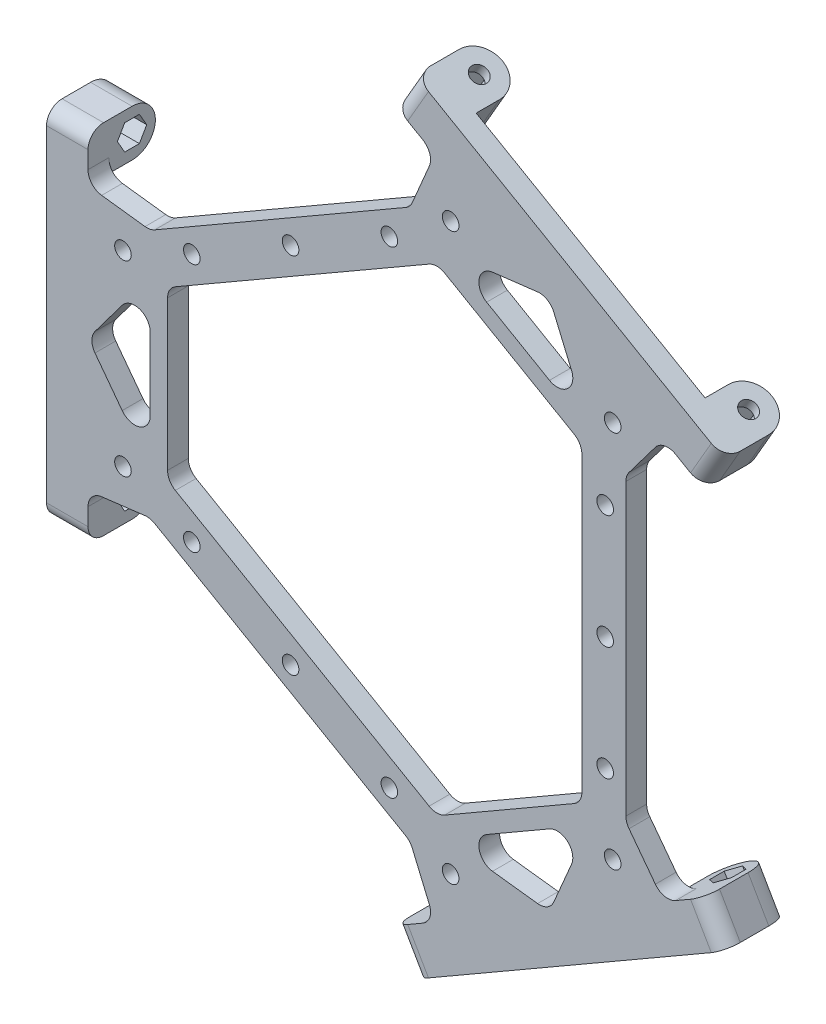
SolidWorks part; units mm, degrees
material "ABS"
ref_plane "前视基准面" through (0, 0, 0) normal (0, 0, 1) x (1, 0, 0)
ref_plane "上视基准面" through (0, 0, 0) normal (0, 1, 0) x (1, 0, 0)
ref_plane "右视基准面" through (0, 0, 0) normal (1, 0, 0) x (0, 0, -1)
sketch "草图1" plane through (0, 0, 0) normal (0, 0, 1) x (1, 0, 0)
  line L0 (0, 0) -> (-67.3124, 0) construction
  line L1 (134.6248, 0) -> (-67.3124, 116.5885)
  line L2 (-67.3124, 116.5885) -> (-67.3124, -116.5885)
  line L3 (-67.3124, -116.5885) -> (134.6248, 0)
  line L4 (-67.3124, 116.5885) -> (-67.3124, 85.5885) construction
  line L5 (-67.3124, 85.5885) -> (-67.3124, 30) construction
  line L6 (0, 0) -> (117.3042, 0) construction
  line L7 (117.3042, 10) -> (117.3042, -10)
  line L8 (-49.9919, -106.5885) -> (-67.3124, -96.5885)
  line L9 (-58.6521, -101.5885) -> (-67.3124, -116.5885) construction
  line L10 (0, 0) -> (-58.6521, -101.5885) construction
  line L11 (-67.3124, 96.5885) -> (-49.9919, 106.5885)
  line L12 (85.9645, 5) -> (-38.6521, 76.9474)
  line L13 (-47.3124, 71.9474) -> (-47.3124, -71.9474)
  line L14 (-38.6521, -76.9474) -> (85.9645, -5)
  line L15 (85.9645, 5) -> (85.9645, -5)
  line L16 (-38.6521, -76.9474) -> (-47.3124, -71.9474)
  line L17 (-47.3124, 71.9474) -> (-38.6521, 76.9474)
  line L18 (94.6248, 0) -> (-47.3124, 81.9474) construction
  line L19 (-47.3124, 81.9474) -> (-47.3124, -81.9474) construction
  line L20 (-47.3124, -81.9474) -> (94.6248, 0) construction
  line L24 (117.3042, 0) -> (134.6248, 0) construction
  line L25 (-58.6521, 101.5885) -> (-67.3124, 116.5885) construction
  line L26 (2.8479, -52.9874) -> (-47.3124, -24.0274)
  line L27 (60.9645, -25.5) -> (60.9645, 25.5) construction
  line L28 (60.9645, 0) -> (40.4645, 0) construction
  line L29 (81.4645, 4.5) -> (81.4645, 7.5981)
  line L30 (81.4645, -4.5) -> (81.4645, -7.5981)
  line L31 (-52.5659, -40.0468) -> (-8.3986, -65.5468) construction
  line L32 (44.4645, 28.96) -> (44.4645, -28.96)
  line L33 (-36.8351, -72.8003) -> (-34.1521, -74.3494)
  line L34 (-44.6294, -68.3003) -> (-47.3124, -66.7513)
  line L35 (0, 0) -> (-58.6521, 101.5885) construction
  line L36 (-47.3124, 24.0274) -> (2.8479, 52.9874)
  line L37 (-8.3986, 65.5468) -> (-52.5659, 40.0468) construction
  line L38 (-44.6294, 68.3003) -> (-47.3124, 66.7513)
  line L39 (-36.8351, 72.8003) -> (-34.1521, 74.3494)
  line L40 (-47.3124, 24.0274) -> (-59.3124, 25.5)
  line L41 (40.4645, 22) -> (40.4645, -22) construction
  line L42 (-47.3124, 16) -> (-59.3124, 0)
  line L43 (-67.3124, 25.5) -> (-47.3124, 25.5) construction
  line L44 (-67.3124, 34.5) -> (-59.3124, 34.5)
  line L45 (-59.3124, 34.5) -> (-59.3124, 25.5)
  line L46 (-59.3124, 25.5) -> (-67.3124, 25.5)
  line L47 (-59.3124, 25.5) -> (-59.3124, -25.5)
  line L48 (-59.3124, -34.5) -> (-59.3124, -25.5)
  line L49 (-59.3124, -25.5) -> (-67.3124, -25.5)
  line L50 (-67.3124, -34.5) -> (-59.3124, -34.5)
  line L51 (-52.5659, 40.0468) -> (-52.5659, 18.0468) construction
  line L52 (-52.5659, -40.0468) -> (-52.5659, -18.0468) construction
  line L53 (60.9645, 25.5) -> (41.9119, 36.5) construction
  line L54 (63.5341, 41.0442) -> (59.5341, 34.116)
  line L55 (-47.3124, -16) -> (-59.3124, 0)
  line L56 (-59.3124, -25.5) -> (-47.3124, -24.0274)
  line L57 (51.7398, 38.616) -> (55.7398, 45.5442)
  line L58 (51.7398, 38.616) -> (7.5725, 64.116)
  line L59 (59.5341, 34.116) -> (51.7398, 38.616)
  line L60 (3.7783, 75.5442) -> (-0.2217, 68.616)
  line L61 (-0.2217, 68.616) -> (7.5725, 64.116)
  line L62 (7.5725, 64.116) -> (11.5725, 71.0442)
  line L63 (7.5725, 64.116) -> (2.8479, 52.9874)
  line L64 (9.7998, 48.9737) -> (29.6562, 51.366)
  line L68 (37.5126, 32.9737) -> (29.6562, 51.366)
  line L69 (-1.1797, -46.0433) -> (-39.2848, -24.0433) construction
  line L70 (44.4645, 28.96) -> (51.7398, 38.616)
  line L71 (-8.3986, -65.5468) -> (10.654, -54.5468) construction
  line L72 (3.7783, -75.5442) -> (-0.2217, -68.616)
  line L73 (7.5725, -64.116) -> (11.5725, -71.0442)
  line L74 (7.5725, -64.116) -> (51.7398, -38.616)
  line L75 (-0.2217, -68.616) -> (7.5725, -64.116)
  line L76 (63.5341, -41.0442) -> (59.5341, -34.116)
  line L77 (59.5341, -34.116) -> (51.7398, -38.616)
  line L78 (51.7398, -38.616) -> (55.7398, -45.5442)
  line L79 (51.7398, -38.616) -> (44.4645, -28.96)
  line L80 (37.5126, -32.9737) -> (29.6562, -51.366)
  line L84 (9.7998, -48.9737) -> (29.6562, -51.366)
  line L85 (-39.2848, 24.0433) -> (-1.1797, 46.0433) construction
  line L86 (2.8479, -52.9874) -> (7.5725, -64.116)
  line L89 (-43.963, 16.1462) -> (7.9985, 46.1462)
  line L90 (35.9645, 30) -> (35.9645, -30)
  line L91 (7.9985, -46.1462) -> (-43.963, -16.1462)
  line L92 (-43.963, 16.1462) -> (-43.963, -16.1462)
  line L93 (7.9985, -46.1462) -> (35.9645, -30)
  line L94 (7.9985, 46.1462) -> (35.9645, 30)
  line L161 (0, 0) -> (-58.6521, -101.5885) construction
  line L162 (0, 0) -> (-58.6521, 101.5885) construction
  circle A0 centre (0, 0) radius 67.3124 construction
  circle A1 centre (-59.9021, 103.7535) radius 2.5
  circle A2 centre (-59.9021, 103.7535) radius 10.3078
  circle A3 centre (119.8042, 0) radius 10.3078
  circle A4 centre (119.8042, 0) radius 2.5
  circle A5 centre (-59.9021, -103.7535) radius 10.3078
  circle A6 centre (-59.9021, -103.7535) radius 2.5
  circle A7 centre (40.4645, 0) radius 1.6
  circle A8 centre (60.9645, 25.5) radius 1.6
  circle A9 centre (81.4645, 0) radius 1.6
  circle A10 centre (81.4645, 0) radius 4.5
  circle A11 centre (60.9645, -25.5) radius 1.6
  circle A22 centre (-20.2323, -35.0433) radius 1.6
  circle A23 centre (-52.5659, -40.0468) radius 1.6
  circle A24 centre (-8.3986, -65.5468) radius 1.6
  circle A25 centre (-40.7323, -70.5503) radius 4.5
  circle A26 centre (-40.7323, -70.5503) radius 1.6
  circle A27 centre (-20.2323, 35.0433) radius 1.6
  circle A28 centre (-8.3986, 65.5468) radius 1.6
  circle A29 centre (-52.5659, 40.0468) radius 1.6
  circle A30 centre (-40.7323, 70.5503) radius 4.5
  circle A31 centre (-40.7323, 70.5503) radius 1.6
  circle A32 centre (40.4645, -22) radius 1.6
  circle A33 centre (40.4645, 22) radius 1.6
  circle A34 centre (-52.5659, 18.0468) radius 1.6
  circle A35 centre (-52.5659, -18.0468) radius 1.6
  circle A36 centre (10.654, 54.5468) radius 1.6
  circle A37 centre (41.9119, 36.5) radius 1.6
  circle A38 centre (-1.1797, -46.0433) radius 1.6
  circle A39 centre (-39.2848, -24.0433) radius 1.6
  circle A40 centre (41.9119, -36.5) radius 1.6
  circle A41 centre (10.654, -54.5468) radius 1.6
  circle A42 centre (-39.2848, 24.0433) radius 1.6
  circle A43 centre (-1.1797, 46.0433) radius 1.6
  point P13 (117.3042, 0)
  point P21 (0, 0)
  point P26 (85.9645, 0)
  point P33 (0, 0)
  point P36 (0, 0)
  point P45 (0, 0)
  point P96 (0, 0)
  point P97 (-17.9823, 31.1462)
  point P98 (0, 0)
  point P104 (-59.3124, 0)
  point P116 (-43.963, 0)
  point P172 (0, 0)
  point P173 (0, 0)
  dimension "D9" = 5
  dimension "D10" = 20.6155
  dimension "D14" = 3.2
  dimension "D15" = 9
  dimension "D19" = 4.5
  dimension "D23" = 3.2
  dimension "D27" = 3.2
  dimension "D1" = 233.1769
  dimension "D2" = 31
  dimension "D4" = 20
  dimension "D7" = 10
  dimension "D5" = 3
  dimension "D12" = 25.5
  dimension "D13" = 20.5
  dimension "D16" = 4
  dimension "D17" = 3
  dimension "D20" = 9
  dimension "D21" = 8
  dimension "D22" = 60
  dimension "D24" = 22
  dimension "D28" = 16
  dimension "D29" = 3
  dimension "D33" = 30
  dimension "D18" = 4.5
  dimension "D25" = 22
  dimension "D6" = 20
  dimension "D8" = 3
  dimension "D11" = 3
  dimension "D26" = 3
ref_plane "基准面4" through (-67.3124, 0, 0) normal (1, 0, 0) x (0, 0, -1)
sketch "草图2" plane through (-67.3124, 0, 0) normal (1, 0, 0) x (0, 0, -1)
  line L0 (0, 0) -> (4.5, 0) construction
  line L1 (0, 5) -> (0, -5) construction
  line L2 (4.5, 0) -> (4.5, 30) construction
  line L3 (4.5, 30) -> (4.5, 70) construction
  line L4 (4.5, 74.5) -> (0, 74.5)
  line L5 (0, 116.5885) -> (0, 85.5885) construction
  line L6 (4.5, 65.5) -> (0, 65.5)
  line L7 (0, 85.5885) -> (0, 30) construction
  line L8 (4.5, 34.5) -> (0, 34.5)
  line L9 (4.5, 25.5) -> (0, 25.5)
  line L10 (0, 71.9474) -> (0, -71.9474) construction
  line L11 (0, 0) -> (18.2138, 0) construction
  line L12 (4.5, -30) -> (4.5, -70) construction
  line L13 (4.5, -25.5) -> (0, -25.5)
  line L14 (4.5, -34.5) -> (0, -34.5)
  line L15 (4.5, -65.5) -> (0, -65.5)
  line L16 (4.5, -74.5) -> (0, -74.5)
  line L17 (0, 0) -> (0, -74.5)
  line L18 (0, 0) -> (0, 74.5)
  circle A0 centre (4.5, 70) radius 4.5
  circle A1 centre (4.5, 30) radius 4.5
  circle A2 centre (4.5, 70) radius 1.6
  circle A3 centre (4.5, 30) radius 1.6
  circle A4 centre (4.5, -30) radius 1.6
  circle A5 centre (4.5, -70) radius 1.6
  circle A6 centre (4.5, -30) radius 4.5
  circle A7 centre (4.5, -70) radius 4.5
  dimension "D4" = 9
  dimension "D5" = 3.2
  dimension "D1" = 4.5
  dimension "D2" = 30
  dimension "D3" = 40
extrude "凸台-拉伸1" add sketch "草图1" along normal blind 4 contours L36 L13 L26 L14 L32 L12 A43 A38 L89 L94 L90 L93 L91 L92 A7 A22 A27 A32 A33 A39 A42 | L12 L70 L58 L68 A37 | L12 L64 L58 L63 A36 | L14 L80 L74 L79 A40 | L14 L86 L74 L84 A41 | L78 L74 L73 L3 | L62 L58 L57 L1 | L59 L54 L1 L57 | L61 L62 L1 L60 | L75 L72 L3 L73 | L77 L78 L3 L76 | L40 L47 L42 L13 A34 | L47 L56 L13 L55 A35 | L49 L47 L46 L2 | L2 L50 L48 L49 | L46 L45 L44 L2
extrude "凸台-拉伸3" add sketch "草图2" along normal blind 8 contours A1 A3 | A1 L18 L9 | A1 L8 L18 | L14 A6 L17 | A6 A4 | L17 A6 L13
sketch3d "3D草图3"
  line L0 (0, 0, 0) -> (0, 0, -186.0312)
pattern_circular "阵列(圆周)1" count 3 over 360 about axis through (0, 0, 0) along (0, 0, 1) of "凸台-拉伸3"
fillet "圆角2" radius 3 33 edges at (7.9985, -46.1462, 2) (35.9645, -30, 2) (35.9645, 30, 2) (7.9985, 46.1462, 2) (-43.963, 16.1462, 2) (-43.963, -16.1462, 2) (-47.3124, 24.0274, 2) (-59.3124, 25.5, 2) (2.8479, 52.9874, 2) (7.5725, 64.116, 2) (51.7398, 38.616, 2) (44.4645, 28.96, 2) (44.4645, -28.96, 2) (51.7398, -38.616, 2) (2.8479, -52.9874, 2) (7.5725, -64.116, 2) (-59.3124, -25.5, 2) (-47.3124, -24.0274, 2) (-47.3124, 16, 2) (-59.3124, 0, 2) (-47.3124, -16, 2) (29.6562, 51.366, 2) (9.7998, 48.9737, 2) (37.5126, 32.9737, 2) (29.6562, -51.366, 2) (37.5126, -32.9737, 2) (9.7998, -48.9737, 2) (1.7783, -72.0801, 4) (61.5341, -37.5801, 4) (61.5341, 37.5801, 4) (1.7783, 72.0801, 4) (-63.3124, -34.5, 4) (-63.3124, 34.5, 4)
sketch "草图4" plane through (-59.3124, 0, 0) normal (1, 0, 0) x (0, 0, -1)
  line L0 (4.5, -30) -> (7.329, -30) construction
  line L1 (7.329, -30) -> (5.9145, -27.55)
  line L2 (5.9145, -27.55) -> (3.0855, -27.55)
  line L3 (3.0855, -27.55) -> (1.671, -30)
  line L4 (1.671, -30) -> (3.0855, -32.45)
  line L5 (3.0855, -32.45) -> (5.9145, -32.45)
  line L6 (5.9145, -32.45) -> (7.329, -30)
  line L7 (0, 0) -> (4.5, 0) construction
  line L8 (4.5, 30) -> (4.5, -30) construction
  line L9 (5.9145, 32.45) -> (7.329, 30)
  line L10 (3.0855, 32.45) -> (5.9145, 32.45)
  line L11 (1.671, 30) -> (3.0855, 32.45)
  line L12 (3.0855, 27.55) -> (1.671, 30)
  line L13 (5.9145, 27.55) -> (3.0855, 27.55)
  line L14 (7.329, 30) -> (5.9145, 27.55)
  circle A0 centre (4.5, -30) radius 2.45 construction
  dimension "D1" = 4.9
extrude "切除-拉伸2" cut sketch "草图4" against normal blind 6
pattern_circular "阵列(圆周)3" count 3 over 360 about axis through (0, 0, 0) along (0, 0, 1) of "切除-拉伸2"
